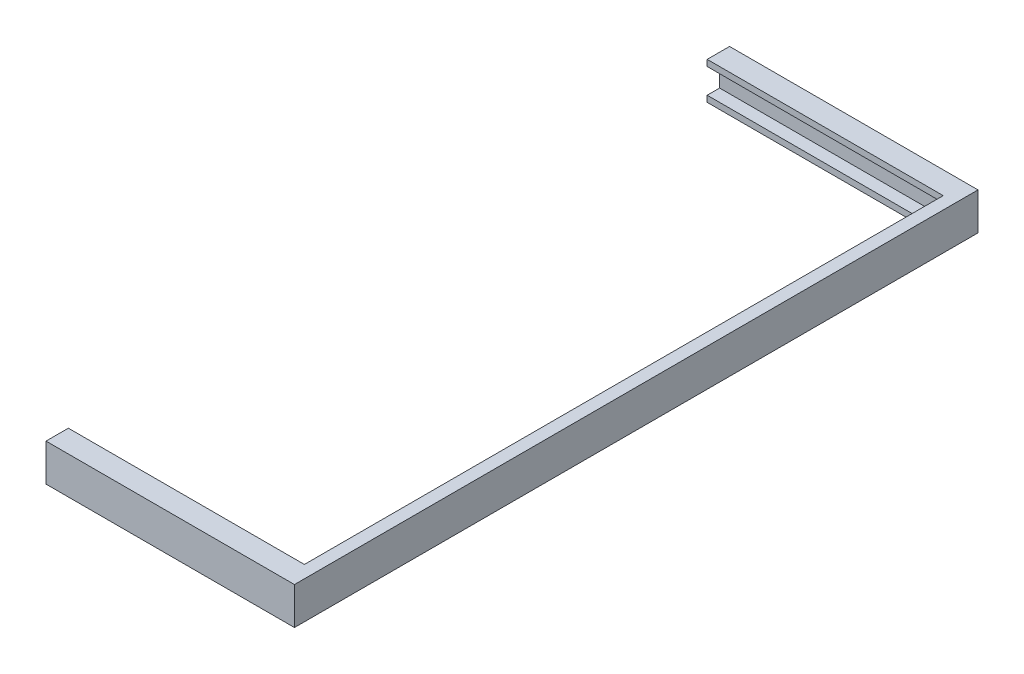
SolidWorks part; units mm, degrees
ref_plane "Plan de face" through (0, 0, 0) normal (0, 0, 1) x (1, 0, 0)
ref_plane "Plan de dessus" through (0, 0, 0) normal (0, 1, 0) x (1, 0, 0)
ref_plane "Plan de droite" through (0, 0, 0) normal (1, 0, 0) x (0, 0, -1)
sketch "Esquisse1" plane through (0, 0, 0) normal (0, 0, 1) x (1, 0, 0)
  line L0 (0, 0) -> (100, 0)
  line L1 (0, 0) -> (0, 15)
  line L2 (0, 15) -> (100, 15)
  line L3 (100, 15) -> (100, 0)
  point P9 (0, 0)
  point P10 (0, 0)
  dimension "D1" = 100
  dimension "D2" = 15
extrude "Boss.-Extru.1" add sketch "Esquisse1" along normal blind 4
sketch "Esquisse2" plane through (0, 0, 4) normal (0, 0, 1) x (1, 0, 0)
  line L4 (0, 12.5) -> (100, 12.5)
  line L5 (117.8913, 7.5) -> (-5.718, 7.5) construction
  line L6 (0, 2.5) -> (100, 2.5)
  line L8 (0, 15) -> (0, 0)
  line L9 (0, 0) -> (100, 0)
  line L10 (100, 0) -> (100, 15)
  line L11 (100, 15) -> (0, 15)
  line L12 (0, 15) -> (0, 0)
  line L13 (0, 0) -> (100, 0)
  line L14 (100, 0) -> (100, 15)
  line L15 (100, 15) -> (0, 15)
  line M7 (0, 15) -> (0, 0)
  line M8 (0, 0) -> (100, 0)
  line M9 (100, 0) -> (100, 15)
  line M10 (100, 15) -> (0, 15)
  dimension "D2" = 2.5
  dimension "D1" = 0
extrude "Boss.-Extru.2" add sketch "Esquisse2" along normal blind 5 contours L4 M7 M9 M10 | L6 M7 M8 M9
sketch "Esquisse3" plane through (0, 0, 4) normal (0, 0, 1) x (1, 0, 0)
  line L0 (95, 15) -> (95, 0)
  line L1 (100, 15) -> (0, 15) construction
  line L2 (0, 0) -> (100, 0) construction
  line L3 (100, 2.5) -> (100, 12.5) construction
  line L4 (100, 15) -> (95, 15)
  line L5 (95, 0) -> (100, 0)
  line L6 (100, 15) -> (100, 0)
  dimension "D1" = 5
extrude "Boss.-Extru.3" add sketch "Esquisse3" along normal blind 267.12
ref_plane "Plan1" through (0, 0, 137.56) normal (0, 0, 1) x (1, 0, 0)
mirror "Symétrie2" about plane through (0, 0, 137.56) normal (0, 0, 1) of "Boss.-Extru.2", "Boss.-Extru.1"
